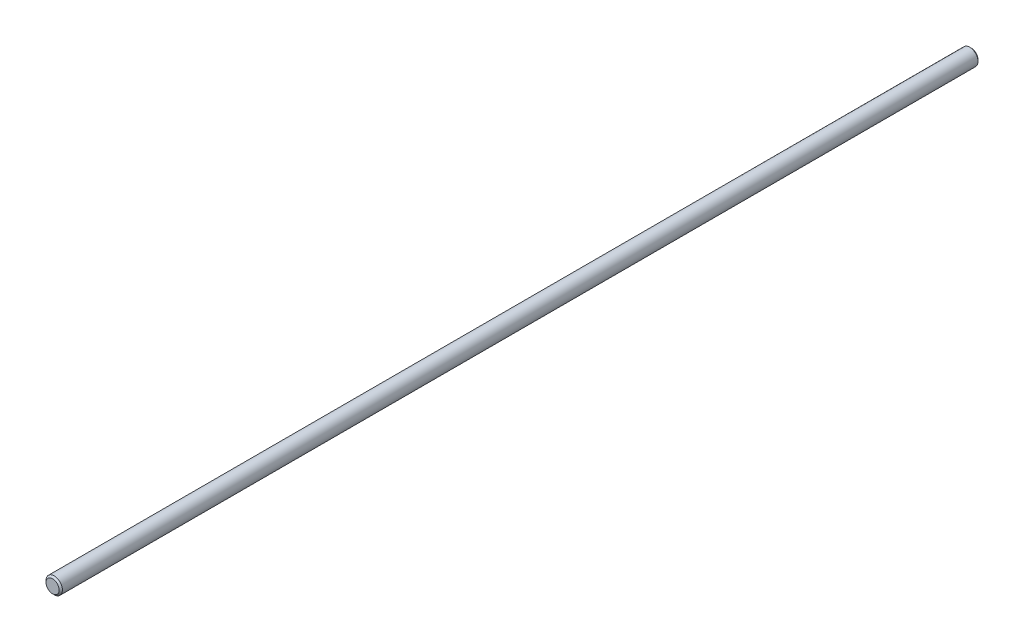
SolidWorks part; units mm, degrees
ref_plane "前视基准面" through (0, 0, 0) normal (0, 0, 1) x (1, 0, 0)
ref_plane "上视基准面" through (0, 0, 0) normal (0, 1, 0) x (1, 0, 0)
ref_plane "右视基准面" through (0, 0, 0) normal (1, 0, 0) x (0, 0, -1)
sketch "草图1" plane through (0, 0, 0) normal (0, 0, 1) x (1, 0, 0)
  circle A0 centre (0, 0) radius 2.5
  dimension "D1" = 5
extrude "凸台-拉伸1" add sketch "草图1" along normal mid plane 280
chamfer "倒角1" distance 0.5 angle 45 2 edges at (2.5, 0, -140) (2.5, 0, 140)
